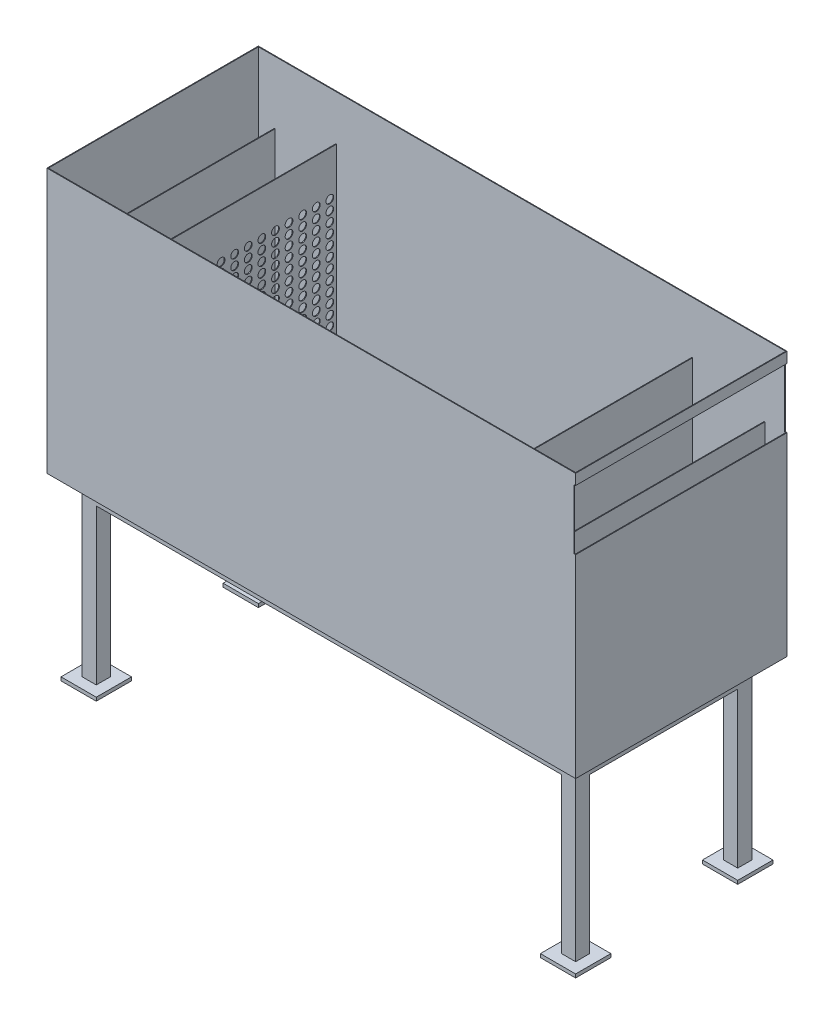
SolidWorks part; units mm, degrees
ref_plane "Спереди" through (0, 0, 0) normal (0, 0, 1) x (1, 0, 0)
ref_plane "Сверху" through (0, 0, 0) normal (0, 1, 0) x (1, 0, 0)
ref_plane "Справа" through (0, 0, 0) normal (1, 0, 0) x (0, 0, -1)
sketch "MASTER_FOOTPRINT" plane through (0, 0, 0) normal (0, 1, 0) x (1, 0, 0)
  line L1 (0, 0) -> (1500, 0)
  line L2 (0, 0) -> (0, 600)
  line L3 (0, 600) -> (1500, 600)
  line L4 (1500, 0) -> (1500, 600)
  dimension "D1" = 1500
  dimension "D2" = 600
extrude "BATH_BASE_PLATE" add sketch "MASTER_FOOTPRINT" along normal blind 750
shell "BATH_SHELL_2MM" thickness 2
sketch "Эскиз1" plane through (0, 0, 0) normal (1, 0, 0) x (0, 0, -1)
  circle A0 centre (300, 420) radius 50
extrude "INLET_D100_OPENING" cut sketch "Эскиз1" along normal blind 10
sketch "Эскиз2" plane through (0, 0, 0) normal (1, 0, 0) x (0, 0, -1)
  line L1 (80, 220) -> (520, 220)
  line L2 (80, 220) -> (80, 650)
  line L3 (80, 650) -> (520, 650)
  line L4 (520, 220) -> (520, 650)
extrude "INLET_IMPACT_BAFFLE" add sketch "Эскиз2" along normal blind 2 from offset 125 separate body
sketch "Эскиз3" plane through (0, 0, 0) normal (1, 0, 0) x (0, 0, -1)
  line L1 (30, 2) -> (570, 2)
  line L2 (30, 2) -> (30, 650)
  line L3 (30, 650) -> (570, 650)
  line L4 (570, 2) -> (570, 650)
  circle A0 centre (49.2857, 125) radius 11
  circle A1 centre (49.2857, 153.5) radius 11
  circle A2 centre (49.2857, 182) radius 11
  circle A3 centre (49.2857, 210.5) radius 11
  circle A4 centre (49.2857, 239) radius 11
  circle A5 centre (49.2857, 267.5) radius 11
  circle A6 centre (49.2857, 296) radius 11
  circle A7 centre (49.2857, 324.5) radius 11
  circle A8 centre (49.2857, 353) radius 11
  circle A9 centre (49.2857, 381.5) radius 11
  circle A10 centre (49.2857, 410) radius 11
  circle A11 centre (49.2857, 438.5) radius 11
  circle A12 centre (49.2857, 467) radius 11
  circle A13 centre (49.2857, 495.5) radius 11
  circle A14 centre (49.2857, 524) radius 11
  circle A15 centre (87.8571, 125) radius 11
  circle A16 centre (87.8571, 153.5) radius 11
  circle A17 centre (87.8571, 182) radius 11
  circle A18 centre (87.8571, 210.5) radius 11
  circle A19 centre (87.8571, 239) radius 11
  circle A20 centre (87.8571, 267.5) radius 11
  circle A21 centre (87.8571, 296) radius 11
  circle A22 centre (87.8571, 324.5) radius 11
  circle A23 centre (87.8571, 353) radius 11
  circle A24 centre (87.8571, 381.5) radius 11
  circle A25 centre (87.8571, 410) radius 11
  circle A26 centre (87.8571, 438.5) radius 11
  circle A27 centre (87.8571, 467) radius 11
  circle A28 centre (87.8571, 495.5) radius 11
  circle A29 centre (87.8571, 524) radius 11
  circle A30 centre (126.4286, 125) radius 11
  circle A31 centre (126.4286, 153.5) radius 11
  circle A32 centre (126.4286, 182) radius 11
  circle A33 centre (126.4286, 210.5) radius 11
  circle A34 centre (126.4286, 239) radius 11
  circle A35 centre (126.4286, 267.5) radius 11
  circle A36 centre (126.4286, 296) radius 11
  circle A37 centre (126.4286, 324.5) radius 11
  circle A38 centre (126.4286, 353) radius 11
  circle A39 centre (126.4286, 381.5) radius 11
  circle A40 centre (126.4286, 410) radius 11
  circle A41 centre (126.4286, 438.5) radius 11
  circle A42 centre (126.4286, 467) radius 11
  circle A43 centre (126.4286, 495.5) radius 11
  circle A44 centre (126.4286, 524) radius 11
  circle A45 centre (165, 125) radius 11
  circle A46 centre (165, 153.5) radius 11
  circle A47 centre (165, 182) radius 11
  circle A48 centre (165, 210.5) radius 11
  circle A49 centre (165, 239) radius 11
  circle A50 centre (165, 267.5) radius 11
  circle A51 centre (165, 296) radius 11
  circle A52 centre (165, 324.5) radius 11
  circle A53 centre (165, 353) radius 11
  circle A54 centre (165, 381.5) radius 11
  circle A55 centre (165, 410) radius 11
  circle A56 centre (165, 438.5) radius 11
  circle A57 centre (165, 467) radius 11
  circle A58 centre (165, 495.5) radius 11
  circle A59 centre (165, 524) radius 11
  circle A60 centre (203.5714, 125) radius 11
  circle A61 centre (203.5714, 153.5) radius 11
  circle A62 centre (203.5714, 182) radius 11
  circle A63 centre (203.5714, 210.5) radius 11
  circle A64 centre (203.5714, 239) radius 11
  circle A65 centre (203.5714, 267.5) radius 11
  circle A66 centre (203.5714, 296) radius 11
  circle A67 centre (203.5714, 324.5) radius 11
  circle A68 centre (203.5714, 353) radius 11
  circle A69 centre (203.5714, 381.5) radius 11
  circle A70 centre (203.5714, 410) radius 11
  circle A71 centre (203.5714, 438.5) radius 11
  circle A72 centre (203.5714, 467) radius 11
  circle A73 centre (203.5714, 495.5) radius 11
  circle A74 centre (203.5714, 524) radius 11
  circle A75 centre (242.1429, 125) radius 11
  circle A76 centre (242.1429, 153.5) radius 11
  circle A77 centre (242.1429, 182) radius 11
  circle A78 centre (242.1429, 210.5) radius 11
  circle A79 centre (242.1429, 239) radius 11
  circle A80 centre (242.1429, 267.5) radius 11
  circle A81 centre (242.1429, 296) radius 11
  circle A82 centre (242.1429, 324.5) radius 11
  circle A83 centre (242.1429, 353) radius 11
  circle A84 centre (242.1429, 381.5) radius 11
  circle A85 centre (242.1429, 410) radius 11
  circle A86 centre (242.1429, 438.5) radius 11
  circle A87 centre (242.1429, 467) radius 11
  circle A88 centre (242.1429, 495.5) radius 11
  circle A89 centre (242.1429, 524) radius 11
  circle A90 centre (280.7143, 125) radius 11
  circle A91 centre (280.7143, 153.5) radius 11
  circle A92 centre (280.7143, 182) radius 11
  circle A93 centre (280.7143, 210.5) radius 11
  circle A94 centre (280.7143, 239) radius 11
  circle A95 centre (280.7143, 267.5) radius 11
  circle A96 centre (280.7143, 296) radius 11
  circle A97 centre (280.7143, 324.5) radius 11
  circle A98 centre (280.7143, 353) radius 11
  circle A99 centre (280.7143, 381.5) radius 11
  circle A100 centre (280.7143, 410) radius 11
  circle A101 centre (280.7143, 438.5) radius 11
  circle A102 centre (280.7143, 467) radius 11
  circle A103 centre (280.7143, 495.5) radius 11
  circle A104 centre (280.7143, 524) radius 11
  circle A105 centre (319.2857, 125) radius 11
  circle A106 centre (319.2857, 153.5) radius 11
  circle A107 centre (319.2857, 182) radius 11
  circle A108 centre (319.2857, 210.5) radius 11
  circle A109 centre (319.2857, 239) radius 11
  circle A110 centre (319.2857, 267.5) radius 11
  circle A111 centre (319.2857, 296) radius 11
  circle A112 centre (319.2857, 324.5) radius 11
  circle A113 centre (319.2857, 353) radius 11
  circle A114 centre (319.2857, 381.5) radius 11
  circle A115 centre (319.2857, 410) radius 11
  circle A116 centre (319.2857, 438.5) radius 11
  circle A117 centre (319.2857, 467) radius 11
  circle A118 centre (319.2857, 495.5) radius 11
  circle A119 centre (319.2857, 524) radius 11
  circle A120 centre (357.8571, 125) radius 11
  circle A121 centre (357.8571, 153.5) radius 11
  circle A122 centre (357.8571, 182) radius 11
  circle A123 centre (357.8571, 210.5) radius 11
  circle A124 centre (357.8571, 239) radius 11
  circle A125 centre (357.8571, 267.5) radius 11
  circle A126 centre (357.8571, 296) radius 11
  circle A127 centre (357.8571, 324.5) radius 11
  circle A128 centre (357.8571, 353) radius 11
  circle A129 centre (357.8571, 381.5) radius 11
  circle A130 centre (357.8571, 410) radius 11
  circle A131 centre (357.8571, 438.5) radius 11
  circle A132 centre (357.8571, 467) radius 11
  circle A133 centre (357.8571, 495.5) radius 11
  circle A134 centre (357.8571, 524) radius 11
  circle A135 centre (396.4286, 125) radius 11
  circle A136 centre (396.4286, 153.5) radius 11
  circle A137 centre (396.4286, 182) radius 11
  circle A138 centre (396.4286, 210.5) radius 11
  circle A139 centre (396.4286, 239) radius 11
  circle A140 centre (396.4286, 267.5) radius 11
  circle A141 centre (396.4286, 296) radius 11
  circle A142 centre (396.4286, 324.5) radius 11
  circle A143 centre (396.4286, 353) radius 11
  circle A144 centre (396.4286, 381.5) radius 11
  circle A145 centre (396.4286, 410) radius 11
  circle A146 centre (396.4286, 438.5) radius 11
  circle A147 centre (396.4286, 467) radius 11
  circle A148 centre (396.4286, 495.5) radius 11
  circle A149 centre (396.4286, 524) radius 11
  circle A150 centre (435, 125) radius 11
  circle A151 centre (435, 153.5) radius 11
  circle A152 centre (435, 182) radius 11
  circle A153 centre (435, 210.5) radius 11
  circle A154 centre (435, 239) radius 11
  circle A155 centre (435, 267.5) radius 11
  circle A156 centre (435, 296) radius 11
  circle A157 centre (435, 324.5) radius 11
  circle A158 centre (435, 353) radius 11
  circle A159 centre (435, 381.5) radius 11
  circle A160 centre (435, 410) radius 11
  circle A161 centre (435, 438.5) radius 11
  circle A162 centre (435, 467) radius 11
  circle A163 centre (435, 495.5) radius 11
  circle A164 centre (435, 524) radius 11
  circle A165 centre (473.5714, 125) radius 11
  circle A166 centre (473.5714, 153.5) radius 11
  circle A167 centre (473.5714, 182) radius 11
  circle A168 centre (473.5714, 210.5) radius 11
  circle A169 centre (473.5714, 239) radius 11
  circle A170 centre (473.5714, 267.5) radius 11
  circle A171 centre (473.5714, 296) radius 11
  circle A172 centre (473.5714, 324.5) radius 11
  circle A173 centre (473.5714, 353) radius 11
  circle A174 centre (473.5714, 381.5) radius 11
  circle A175 centre (473.5714, 410) radius 11
  circle A176 centre (473.5714, 438.5) radius 11
  circle A177 centre (473.5714, 467) radius 11
  circle A178 centre (473.5714, 495.5) radius 11
  circle A179 centre (473.5714, 524) radius 11
  circle A180 centre (512.1429, 125) radius 11
  circle A181 centre (512.1429, 153.5) radius 11
  circle A182 centre (512.1429, 182) radius 11
  circle A183 centre (512.1429, 210.5) radius 11
  circle A184 centre (512.1429, 239) radius 11
  circle A185 centre (512.1429, 267.5) radius 11
  circle A186 centre (512.1429, 296) radius 11
  circle A187 centre (512.1429, 324.5) radius 11
  circle A188 centre (512.1429, 353) radius 11
  circle A189 centre (512.1429, 381.5) radius 11
  circle A190 centre (512.1429, 410) radius 11
  circle A191 centre (512.1429, 438.5) radius 11
  circle A192 centre (512.1429, 467) radius 11
  circle A193 centre (512.1429, 495.5) radius 11
  circle A194 centre (512.1429, 524) radius 11
  circle A195 centre (550.7143, 125) radius 11
  circle A196 centre (550.7143, 153.5) radius 11
  circle A197 centre (550.7143, 182) radius 11
  circle A198 centre (550.7143, 210.5) radius 11
  circle A199 centre (550.7143, 239) radius 11
  circle A200 centre (550.7143, 267.5) radius 11
  circle A201 centre (550.7143, 296) radius 11
  circle A202 centre (550.7143, 324.5) radius 11
  circle A203 centre (550.7143, 353) radius 11
  circle A204 centre (550.7143, 381.5) radius 11
  circle A205 centre (550.7143, 410) radius 11
  circle A206 centre (550.7143, 438.5) radius 11
  circle A207 centre (550.7143, 467) radius 11
  circle A208 centre (550.7143, 495.5) radius 11
  circle A209 centre (550.7143, 524) radius 11
extrude "DISTRIBUTOR_D22" add sketch "Эскиз3" along normal blind 2 from offset 250 separate body
sketch "Эскиз4" plane through (0, 0, 0) normal (1, 0, 0) x (0, 0, -1)
  line L1 (50, 320) -> (550, 320)
  line L2 (50, 320) -> (50, 650)
  line L3 (50, 650) -> (550, 650)
  line L4 (550, 320) -> (550, 650)
extrude "OUTLET_SUBMERGED_BAFFLE" add sketch "Эскиз4" along normal blind 2 from offset 1280 separate body
sketch "Эскиз5" plane through (0, 0, 0) normal (1, 0, 0) x (0, 0, -1)
  line L1 (5, 2) -> (595, 2)
  line L2 (5, 2) -> (5, 550)
  line L3 (5, 550) -> (595, 550)
  line L4 (595, 2) -> (595, 550)
extrude "OVERFLOW_WEIR_Z550" add sketch "Эскиз5" along normal blind 2 from offset 1440 separate body
sketch "Эскиз6" plane through (0, 0, 0) normal (1, 0, 0) x (0, 0, -1)
  line L0 (0, 750) -> (0, 0) construction
  line L1 (0, 550) -> (600, 550)
  line L2 (0, 550) -> (0, 720)
  line L3 (0, 720) -> (600, 720)
  line L4 (600, 550) -> (600, 720)
  line L5 (600, 750) -> (600, 0) construction
extrude "OUTLET_WEIR_SLOT_W600" cut sketch "Эскиз6" along normal blind 10 from offset 1495
sketch "Эскиз7" plane through (0, 0, 0) normal (1, 0, 0) x (0, 0, -1)
  line L0 (2, -1) -> (2, 120)
  line L1 (2, 120) -> (230, -1)
  line L2 (230, -1) -> (2, -1)
  line L3 (598, -1) -> (598, 120)
  line L4 (598, 120) -> (370, -1)
  line L5 (370, -1) -> (598, -1)
extrude "SLOPED_SEDIMENT_FLOOR" add sketch "Эскиз7" along normal blind 975 from offset 275
sketch3d "SCREW_AXIS_30DEG_REFERENCE"
  line L0 (400, 70, -300) -> (1600, 762.8203, -300)
sketch "Эскиз8" plane through (0, 0, 0) normal (0, 1, 0) x (1, 0, 0)
  line L1 (50, 50) -> (90, 50)
  line L2 (50, 50) -> (50, 90)
  line L3 (50, 90) -> (90, 90)
  line L4 (90, 50) -> (90, 90)
  line L6 (50, 510) -> (90, 510)
  line L7 (50, 510) -> (50, 550)
  line L8 (50, 550) -> (90, 550)
  line L9 (90, 510) -> (90, 550)
  line L11 (1410, 50) -> (1450, 50)
  line L12 (1410, 50) -> (1410, 90)
  line L13 (1410, 90) -> (1450, 90)
  line L14 (1450, 50) -> (1450, 90)
  line L16 (1410, 510) -> (1450, 510)
  line L17 (1410, 510) -> (1410, 550)
  line L18 (1410, 550) -> (1450, 550)
  line L19 (1450, 510) -> (1450, 550)
extrude "FRAME_LEGS_40X40_H500" add sketch "Эскиз8" against normal blind 500
sketch "Эскиз9" plane through (0, 0, 0) normal (0, 1, 0) x (1, 0, 0)
  line L1 (50, 50) -> (1450, 50)
  line L2 (50, 50) -> (50, 90)
  line L3 (50, 90) -> (1450, 90)
  line L4 (1450, 50) -> (1450, 90)
  line L6 (50, 510) -> (1450, 510)
  line L7 (50, 510) -> (50, 550)
  line L8 (50, 550) -> (1450, 550)
  line L9 (1450, 510) -> (1450, 550)
extrude "FRAME_LONGITUDINAL_RAILS" add sketch "Эскиз9" against normal blind 40 from offset 20
sketch "Эскиз10" plane through (0, 0, 0) normal (0, 1, 0) x (1, 0, 0)
  line L1 (50, 90) -> (90, 90)
  line L2 (50, 90) -> (50, 510)
  line L3 (50, 510) -> (90, 510)
  line L4 (90, 90) -> (90, 510)
  line L6 (1410, 90) -> (1450, 90)
  line L7 (1410, 90) -> (1410, 510)
  line L8 (1410, 510) -> (1450, 510)
  line L9 (1450, 90) -> (1450, 510)
extrude "FRAME_TRANSVERSE_RAILS" add sketch "Эскиз10" against normal blind 40 from offset 20
sketch "Эскиз11" plane through (0, 0, 0) normal (0, 1, 0) x (1, 0, 0)
  line L1 (20, 20) -> (120, 20)
  line L2 (20, 20) -> (20, 120)
  line L3 (20, 120) -> (120, 120)
  line L4 (120, 20) -> (120, 120)
  line L6 (20, 480) -> (120, 480)
  line L7 (20, 480) -> (20, 580)
  line L8 (20, 580) -> (120, 580)
  line L9 (120, 480) -> (120, 580)
  line L11 (1380, 20) -> (1480, 20)
  line L12 (1380, 20) -> (1380, 120)
  line L13 (1380, 120) -> (1480, 120)
  line L14 (1480, 20) -> (1480, 120)
  line L16 (1380, 480) -> (1480, 480)
  line L17 (1380, 480) -> (1380, 580)
  line L18 (1380, 580) -> (1480, 580)
  line L19 (1480, 480) -> (1480, 580)
extrude "FRAME_FOOT_PADS_100X100" add sketch "Эскиз11" against normal blind 10 from offset 500
equation "\"AI_Q_Peak\"= 0.006"
equation "\"AI_B_Bath\" = 600"
equation "\"AI_L_Settle\" = 1050"
equation "\"AI_L_Inlet\"= 250"
equation "\"AI_L_Outlet\"= 200"
equation "\"AI_L_Bath\" = 1500"
equation "\"AI_H_Water\"= 550"
equation "\"AI_H_Freeboard\"= 200"
equation "\"AI_H_Bath\"= 750"
equation "\"AI_Shell_Thickness\"= 2"
equation "\"AI_Inlet_DN\"= 100"
equation "\"AI_Weir_Width\"= 600"
equation "\"AI_Inlet_Baffle_Offset\"= 125"
equation "\"AI_Distributor_Open_Area\"= 0.28"
equation "\"AI_Distributor_Hole_Dia\"= 22"
equation "\"AI_Distributor_Blind_Zone\"= 110"
equation "\"AI_Outlet_Baffle_Depth\"= 250"
equation "\"AI_Screw_Diameter\"= 100"
equation "\"AI_Screw_Pitch\"= 100"
equation "\"AI_Screw_Angle\"= 30"
equation "\"AI_Screw_Rpm\"= 15"
equation "\"AI_Screw_Clearance\"= 5"
equation "\"AI_Liner_Thickness\"= 5"
equation "\"AI_Discharge_Height\"= 650"
equation "\"AI_Frame_Height\"= 500"
equation "\"D1@MASTER_FOOTPRINT\" = \"AI_L_Bath\""
equation "\"D2@MASTER_FOOTPRINT\" = \"AI_B_Bath\""
equation "\"D1@BATH_BASE_PLATE\" = \"AI_H_Bath\""
